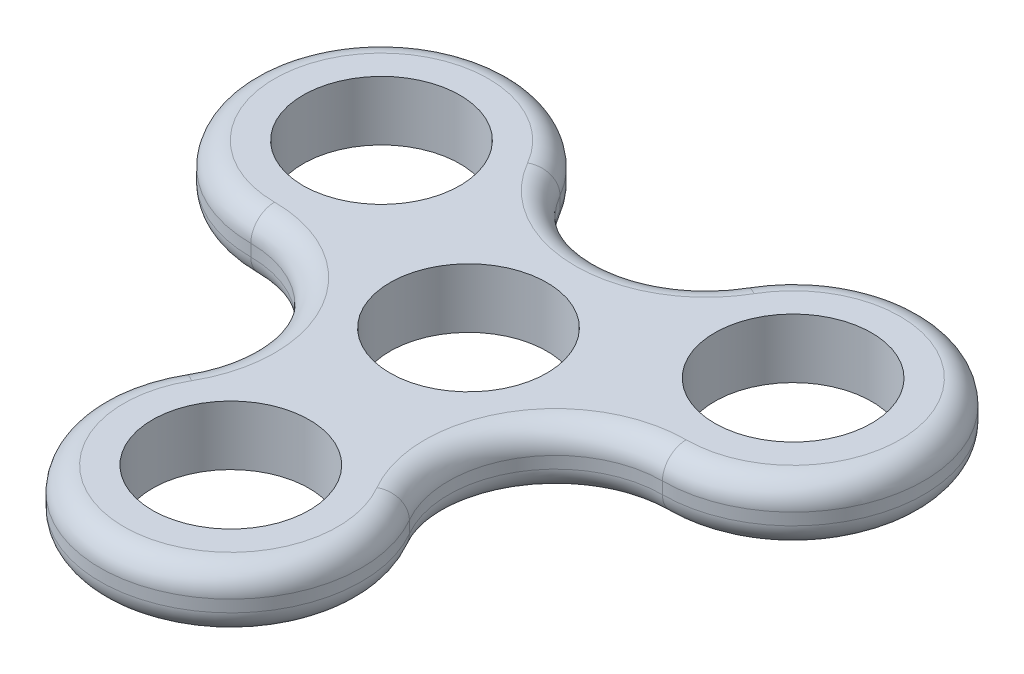
SolidWorks part; units mm, degrees
ref_plane "Alzado" through (0, 0, 0) normal (0, 0, 1) x (1, 0, 0)
ref_plane "Planta" through (0, 0, 0) normal (0, 1, 0) x (1, 0, 0)
ref_plane "Vista lateral" through (0, 0, 0) normal (1, 0, 0) x (0, 0, -1)
sketch "Croquis1" plane through (0, 0, 0) normal (0, 1, 0) x (1, 0, 0)
  line L0 (0, -20) -> (0, 20) construction
  line L1 (17.3205, -10) -> (-17.3205, 10) construction
  line L2 (17.3205, 10) -> (-17.3205, -10) construction
  circle A0 centre (0, 0) radius 7 construction
  circle A1 centre (0, -20) radius 7 construction
  circle A2 centre (-17.3205, 10) radius 7 construction
  circle A3 centre (17.3205, 10) radius 7 construction
  arc A4 (17.3205, -1) -> (7.7942, 15.5) centre (17.3205, 10) ccw
  arc A5 (-9.5263, -14.5) -> (9.5263, -14.5) centre (0, -20) ccw
  arc A6 (-7.7942, 15.5) -> (-17.3205, -1) centre (-17.3205, 10) ccw
  circle A7 centre (0, 0) radius 20 construction
  arc A8 (-9.5263, -14.5) -> (-17.3205, -1) centre (-17.3205, -10) ccw
  arc A9 (17.3205, -1) -> (9.5263, -14.5) centre (17.3205, -10) ccw
  arc A10 (-7.7942, 15.5) -> (7.7942, 15.5) centre (0, 20) ccw
  circle A11 centre (0, 0) radius 6.6
  circle A12 centre (17.3205, 10) radius 11 construction
  circle A13 centre (-17.3205, 10) radius 11 construction
  circle A14 centre (0, -20) radius 11 construction
  circle A15 centre (0, -20) radius 6.6
  circle A16 centre (17.3205, 10) radius 6.6
  circle A17 centre (-17.3205, 10) radius 6.6
  point P6 (0, 0)
  point P9 (-16.8875, -9.75)
  point P10 (9.5, 19.5)
  point P11 (17.5492, -10.132)
  point P12 (-7.3875, -9.75)
  point P13 (0, 4.875)
  point P17 (26.3875, -9.75)
  point P27 (28.3205, 10)
  point P30 (11, -20)
  point P32 (-6.3205, 10)
  dimension "D1" = 60
  dimension "D3" = 4
  dimension "D2" = 60
extrude "Saliente-Extruir1" add sketch "Croquis1" along normal blind 5
fillet "Redondeo1" radius 2 12 edges at (26.8468, 5, -15.5) (9.5263, 5, 5.5) (0, 5, 31) (-9.5263, 5, 5.5) (-26.8468, 5, -15.5) (26.8468, 0, -15.5) (9.5263, 0, 5.5) (0, 0, 31) (-9.5263, 0, 5.5) (-26.8468, 0, -15.5) (0, 5, -11) (0, 0, -11)
